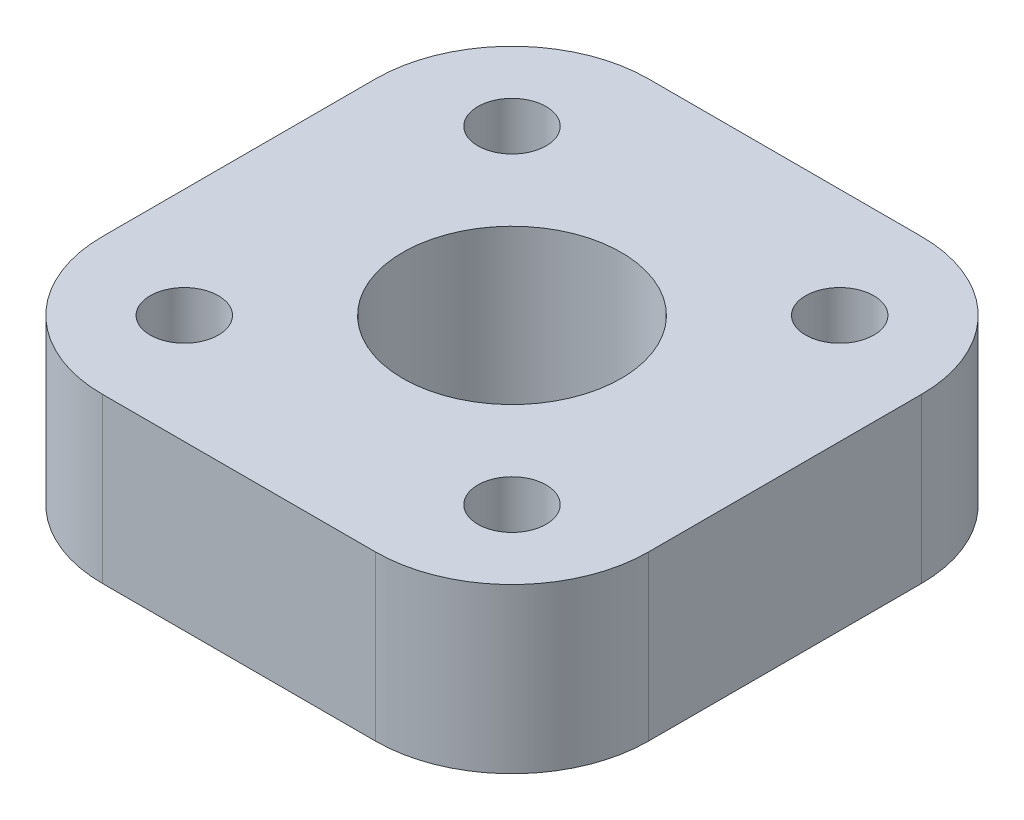
SolidWorks part; units mm, degrees
material "6061-T6 (SS)"
ref_plane "Alzado" through (0, 0, 0) normal (0, 0, 1) x (1, 0, 0)
ref_plane "Planta" through (0, 0, 0) normal (0, 1, 0) x (1, 0, 0)
ref_plane "Vista lateral" through (0, 0, 0) normal (1, 0, 0) x (0, 0, -1)
sketch "Croquis1" plane through (0, 0, 0) normal (0, 1, 0) x (1, 0, 0)
  line L1 (-10, -10) -> (10, -10)
  line L2 (-10, -10) -> (-10, 10)
  line L3 (-10, 10) -> (10, 10)
  line L4 (10, -10) -> (10, 10)
  line L5 (-10, -10) -> (10, 10) construction
  line L6 (-10, 10) -> (10, -10) construction
  circle A0 centre (0, 0) radius 4
  point P0 (0, 0)
  dimension "D2" = 8
  dimension "D1" = 20
extrude "Saliente-Extruir1" add sketch "Croquis1" along normal mid plane 6
hole_wizard "Taladro roscado M3x0.52" positions "Croquis2" profile "Croquis3" tap size "M3x0.5" standard "Ansi Metric" end condition up to next
sketch "Croquis2" plane through (0, 3, 0) normal (0, 1, 0) x (1, 0, 0)
  line L1 (6, -6) -> (-6, -6) construction
  line L2 (6, -6) -> (6, 6) construction
  line L3 (6, 6) -> (-6, 6) construction
  line L4 (-6, -6) -> (-6, 6) construction
  line L5 (6, -6) -> (-6, 6) construction
  line L6 (6, 6) -> (-6, -6) construction
  point P0 (6, 6)
  point P3 (-6, 6)
  point P6 (-6, -6)
  point P9 (6, -6)
  point P54 (0, 0)
  dimension "D1" = 12
sketch "Croquis3" plane through (6, 3, -6) normal (1, 0, 0) x (0, 0, 1)
  line L0 (0, 0) -> (0, 6)
  line L1 (0, 6) -> (1.25, 6)
  line L2 (1.25, 6) -> (1.25, 0)
  line L5 (1.25, 0) -> (0, 0)
  line L11 (0, -6.35) -> (0, 107.95) construction
  dimension "Diámetro de perforador para roscar hasta el siguiente" = 2.5
  dimension "Profundidad de perforador para roscar hasta el siguiente" = 6
cosmetic thread "Rosca de taladro2" parameters "D2"=3
cosmetic thread "Rosca de taladro3" parameters "D2"=3
cosmetic thread "Rosca de taladro4" parameters "D2"=3
cosmetic thread "Rosca de taladro5" parameters "D2"=3
fillet "Redondeo1" radius 5 4 edges at (10, 0, -10) (10, 0, 10) (-10, 0, -10) (-10, 0, 10)
